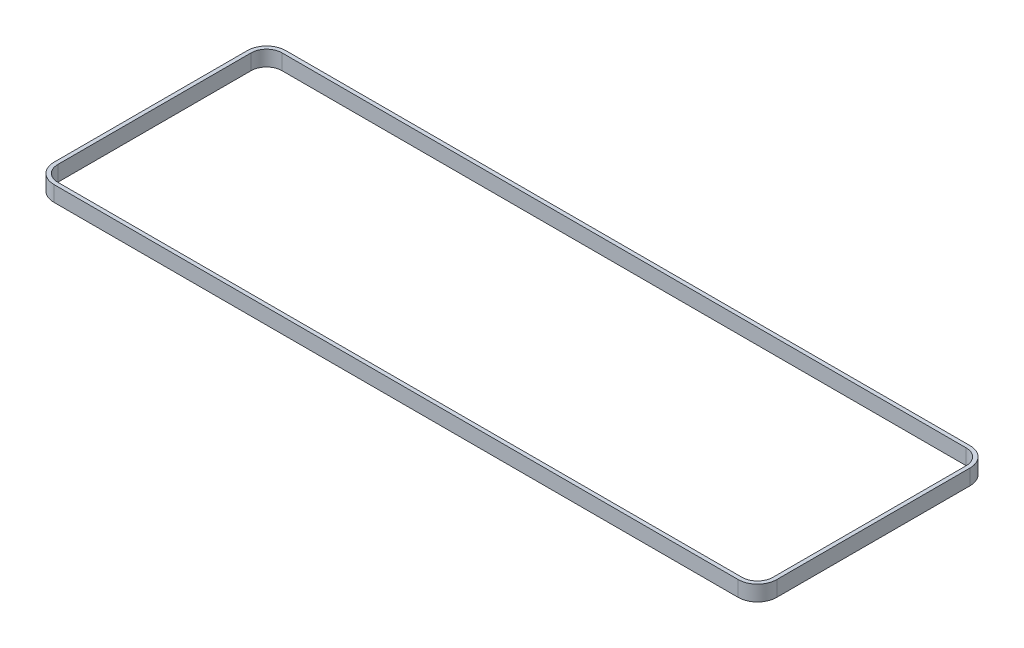
SolidWorks part; units mm, degrees
ref_plane "Front Plane" through (0, 0, 0) normal (0, 0, 1) x (1, 0, 0)
ref_plane "Top Plane" through (0, 0, 0) normal (0, 1, 0) x (1, 0, 0)
ref_plane "Right Plane" through (0, 0, 0) normal (1, 0, 0) x (0, 0, -1)
sketch "Sketch1" plane through (0, 0, 0) normal (0, 1, 0) x (1, 0, 0)
  line L0 (-112.395, 38.1) -> (112.395, 38.1)
  line L1 (-112.395, -36.83) -> (112.395, -36.83)
  line L2 (-117.475, -31.75) -> (-117.475, 31.75)
  line L3 (-112.395, 36.83) -> (112.395, 36.83)
  line L4 (117.475, -31.75) -> (117.475, 31.75)
  line L5 (-117.475, -36.83) -> (117.475, 36.83) construction
  line L6 (-117.475, 36.83) -> (117.475, -36.83) construction
  line L7 (118.745, -31.75) -> (118.745, 31.75)
  line L8 (-112.395, -38.1) -> (112.395, -38.1)
  line L9 (-118.745, -31.75) -> (-118.745, 31.75)
  arc A0 (112.395, 36.83) -> (117.475, 31.75) centre (112.395, 31.75) cw
  arc A1 (117.475, -31.75) -> (112.395, -36.83) centre (112.395, -31.75) cw
  arc A2 (-112.395, -36.83) -> (-117.475, -31.75) centre (-112.395, -31.75) cw
  arc A3 (-112.395, 36.83) -> (-117.475, 31.75) centre (-112.395, 31.75) ccw
  arc A4 (112.395, 38.1) -> (118.745, 31.75) centre (112.395, 31.75) cw
  arc A5 (118.745, -31.75) -> (112.395, -38.1) centre (112.395, -31.75) cw
  arc A6 (-112.395, -38.1) -> (-118.745, -31.75) centre (-112.395, -31.75) cw
  arc A7 (-112.395, 38.1) -> (-118.745, 31.75) centre (-112.395, 31.75) ccw
  point P0 (0, 0)
  dimension "D3" = 5.08
  dimension "D1" = 73.66
  dimension "D2" = 234.95
  dimension "D4" = 1.27
extrude "Boss-Extrude1" add sketch "Sketch1" along normal blind 5.08
